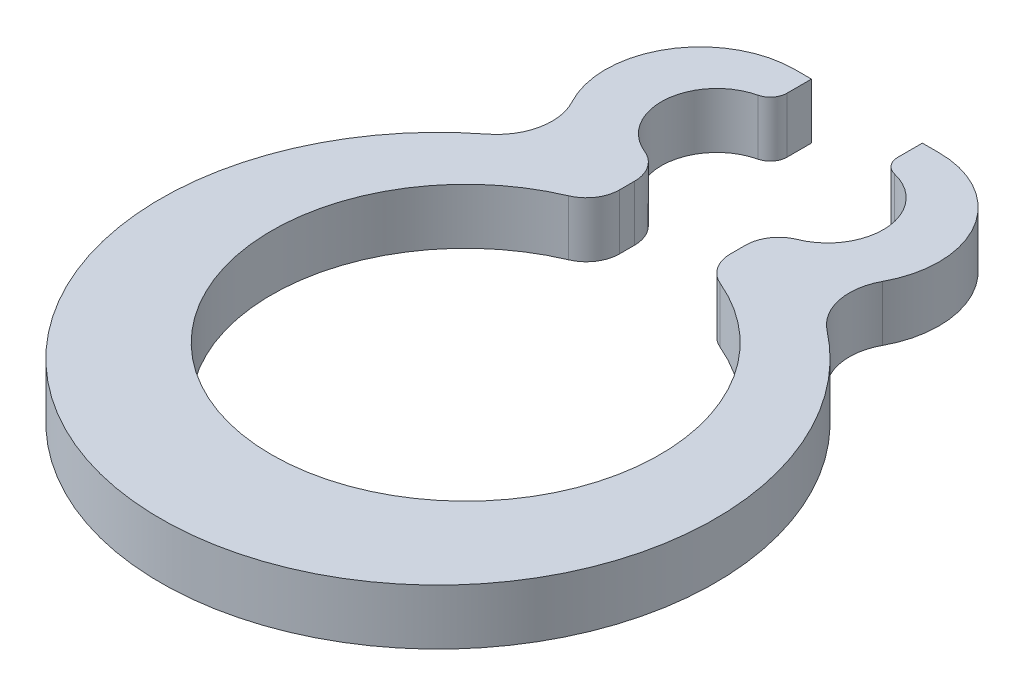
SolidWorks part; units mm, degrees
ref_plane "Спереди" through (0, 0, 0) normal (0, 0, 1) x (1, 0, 0)
ref_plane "Сверху" through (0, 0, 0) normal (0, 1, 0) x (1, 0, 0)
ref_plane "Справа" through (0, 0, 0) normal (1, 0, 0) x (0, 0, -1)
sketch "Эскиз1" plane through (0, 0, 0) normal (0, 1, 0) x (1, 0, 0)
  line L1 (-0.5, 3.3965) -> (-0.5, 3.6173)
  line L6 (0.5, 3.6173) -> (0.65, 3.6173)
  line L7 (-0.65, 3.6173) -> (-0.5, 3.6173)
  line L9 (0.5, 3.3965) -> (0.5, 3.6173)
  line L11 (0.5, 1.8875) -> (0.5, 2.0225)
  line L13 (-0.5, 1.8875) -> (-0.5, 2.0225)
  arc A0 (-0.6829, 1.6112) -> (0.6829, 1.6112) centre (0, 0) ccw
  arc A2 (-1.5332, 1.7247) -> (1.5332, 1.7247) centre (0, -0.25) ccw
  arc A5 (-0.6154, 3.2506) -> (-0.6875, 2.3006) centre (-0.5, 2.7641) ccw
  arc A6 (0.6875, 2.3006) -> (0.6154, 3.2506) centre (0.5, 2.7641) ccw
  arc A7 (-0.65, 3.6173) -> (-1.4002, 2.3577) centre (-0.65, 2.7641) ccw
  arc A8 (1.4002, 2.3577) -> (0.65, 3.6173) centre (0.65, 2.7641) ccw
  arc A9 (1.4002, 2.3577) -> (1.5332, 1.7247) centre (1.8399, 2.1196) ccw
  arc A10 (-1.4002, 2.3577) -> (-1.5332, 1.7247) centre (-1.8399, 2.1196) cw
  arc A11 (0.5, 2.0225) -> (0.6875, 2.3006) centre (0.8, 2.0225) cw
  arc A12 (0.5, 1.8875) -> (0.6829, 1.6112) centre (0.8, 1.8875) ccw
  arc A13 (-0.5, 1.8875) -> (-0.6829, 1.6112) centre (-0.8, 1.8875) cw
  arc A14 (-0.5, 2.0225) -> (-0.6875, 2.3006) centre (-0.8, 2.0225) ccw
  arc A15 (0.5, 3.3965) -> (0.6154, 3.2506) centre (0.65, 3.3965) ccw
  arc A16 (-0.5, 3.3965) -> (-0.6154, 3.2506) centre (-0.65, 3.3965) cw
  point P5 (0, 0)
  point P9 (0, 0)
  point P19 (0, 0)
  dimension "D1" = 3.5
  dimension "D2" = 5
  dimension "D4" = 0.5
  dimension "D5" = 1
  dimension "D7" = 1.3
  dimension "D6" = 0.5
  dimension "D8" = 0.3
  dimension "D9" = 0.15
  dimension "D3" = 0.25
extrude "Бобышка-Вытянуть1" add sketch "Эскиз1" along normal blind 0.5
